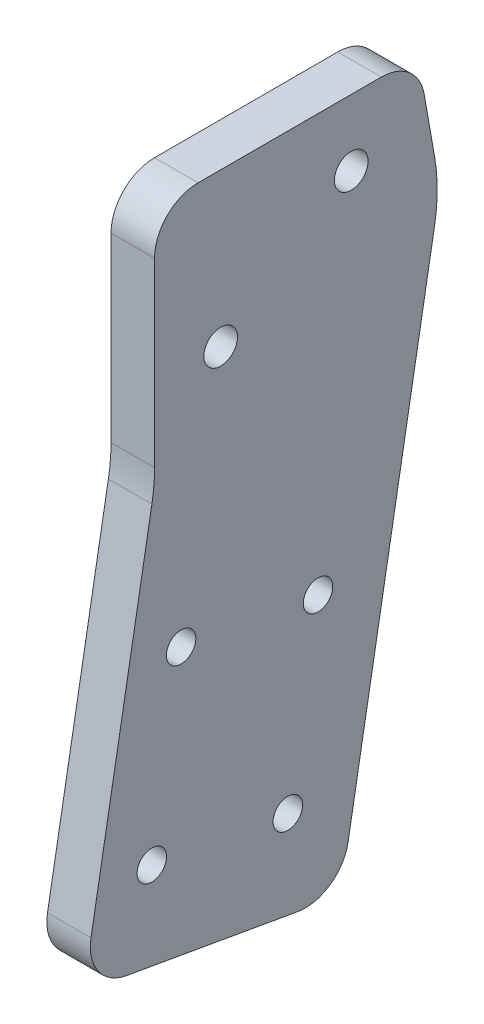
SolidWorks part; units mm, degrees
material "6061-T6 (SS)"
ref_plane "Front Plane" through (0, 0, 0) normal (0, 0, 1) x (1, 0, 0)
ref_plane "Top Plane" through (0, 0, 0) normal (0, 1, 0) x (1, 0, 0)
ref_plane "Right Plane" through (0, 0, 0) normal (1, 0, 0) x (0, 0, -1)
sketch "Sketch1" plane through (5.0358, 0, 0) normal (-1, 0, 0) x (0, 0, 1)
  line L0 (-147.7756, 230.0705) -> (-162.2698, 312.271)
  line L1 (-162.2698, 312.271) -> (-159.0451, 330.559)
  line L2 (-159.0451, 330.559) -> (-120.6268, 330.559)
  line L3 (-120.6268, 330.559) -> (-120.6268, 295.5112)
  line L4 (-147.7756, 230.0705) -> (-110.2544, 236.6865)
  line L5 (-139.5479, 183.4086) -> (-158.6812, 291.9191) construction
  line L6 (-110.2544, 236.6865) -> (-120.6268, 295.5112)
  line L7 (-72.8031, 24.2892) -> (-117.5036, 277.7986) construction
  line L8 (-126.9495, 330.559) -> (-152.9373, 330.559) construction
  circle A0 centre (-140.0751, 244.3242) radius 2.1527 construction
  dimension "D3" = 12.7
  dimension "D1" = 0
  dimension "D2" = 0
  dimension "D4" = 100
  dimension "D5" = 18.288
extrude "Boss-Extrude1" add sketch "Sketch1" along normal blind 6.35
fillet "Fillet1" radius 25.4 2 edges at (1.8608, 295.5112, -120.6268) (1.8608, 312.271, -162.2698)
hole_wizard "CSK for #6 Flat Head Machine Screw (100)1" positions "Sketch3" profile "Sketch2" countersink size "#6" standard "ANSI Inch" end condition through all
sketch "Sketch3" plane through (-1.3142, 0, 0) normal (-1, 0, 0) x (0, 0, 1)
  point P0 (-124.5041, 273.1394)
  point P3 (-144.4852, 269.7242)
  point P6 (-140.0751, 244.3242)
  point P9 (-120.2274, 247.7166)
sketch "Sketch2" plane through (-1.3142, 273.1394, -124.5041) normal (0, 1, 0) x (0, 0, 1)
  line L0 (0, 0) -> (0, 6.35)
  line L1 (0, 6.35) -> (2.1526, 6.35)
  line L2 (2.1526, 6.35) -> (2.1526, 1.1669)
  line L3 (2.1526, 1.1669) -> (3.5433, 0)
  line L5 (3.5433, 0) -> (0, 0)
  line L6 (-2.1526, 1.1669) -> (-3.5433, 0) construction
  line L11 (0, -6.35) -> (0, 107.95) construction
  dimension "Thru Hole Dia." = 4.3053
  dimension "Thru Hole Depth" = 6.35
  dimension "Near C'Sink Dia." = 7.0866
  dimension "Near C'Sink Angle" = 100
hole_wizard "CSK for #8 Flat Head Machine Screw (100)1" positions "Sketch4" profile "Sketch5" countersink size "#8" standard "ANSI Inch" end condition through all
sketch "Sketch4" plane through (-1.3142, 0, 0) normal (-1, 0, 0) x (0, 0, 1)
  point P0 (-149.3288, 320.907)
  point P2 (-130.2788, 308.207)
sketch "Sketch5" plane through (-1.3142, 320.907, -149.3288) normal (0, 1, 0) x (0, 0, 1)
  line L0 (0, 0) -> (0, 6.35)
  line L1 (0, 6.35) -> (2.4574, 6.35)
  line L2 (2.4574, 6.35) -> (2.4574, 1.4759)
  line L3 (2.4574, 1.4759) -> (4.2164, 0)
  line L5 (4.2164, 0) -> (0, 0)
  line L6 (-2.4574, 1.4759) -> (-4.2164, 0) construction
  line L11 (0, -6.35) -> (0, 107.95) construction
  dimension "Thru Hole Dia." = 4.9149
  dimension "Thru Hole Depth" = 6.35
  dimension "Near C'Sink Dia." = 8.4328
  dimension "Near C'Sink Angle" = 100
chamfer "Chamfer1" [suppressed] distance 2.54 angle 45
chamfer "Chamfer2" [suppressed] distance 6.35 angle 45
fillet "Fillet2" radius 6.35 4 edges at (1.8608, 330.559, -120.6268) (1.8608, 330.559, -159.0451) (1.8608, 236.6865, -110.2544) (1.8608, 230.0705, -147.7756)
